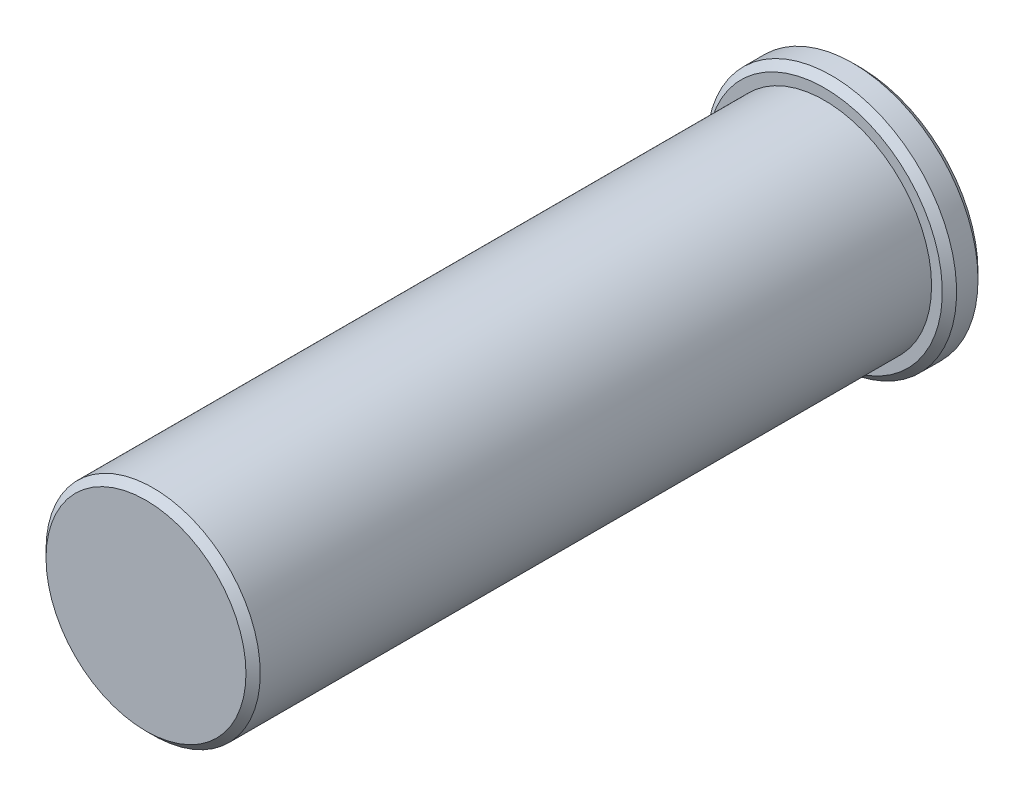
SolidWorks part; units mm, degrees
ref_plane "前视基准面" through (0, 0, 0) normal (0, 0, 1) x (1, 0, 0)
ref_plane "上视基准面" through (0, 0, 0) normal (0, 1, 0) x (1, 0, 0)
ref_plane "右视基准面" through (0, 0, 0) normal (1, 0, 0) x (0, 0, -1)
sketch "草图1" plane through (0, 0, 0) normal (0, 0, 1) x (1, 0, 0)
  circle A0 centre (0, 0) radius 1.5
  dimension "D1" = 3
extrude "凸台-拉伸1" add sketch "草图1" along normal blind 10
sketch "草图2" plane through (0, 0, 0) normal (0, 0, -1) x (-1, 0, 0)
  circle A0 centre (0, 0) radius 1.75
  dimension "D1" = 3.5
extrude "凸台-拉伸2" add sketch "草图2" against normal blind 0.5
chamfer "倒角1" distance 0.1 angle 45 3 edges at (-1.75, 0, 0) (-1.75, 0, 0.5) (1.5, 0, 10)
sketch "草图3" plane through (0, 0, 0) normal (0, 0, -1) x (-1, 0, 0)
  circle A0 centre (0, 0) radius 1
  dimension "D1" = 2
extrude "切除-拉伸1" cut sketch "草图3" against normal blind 5
